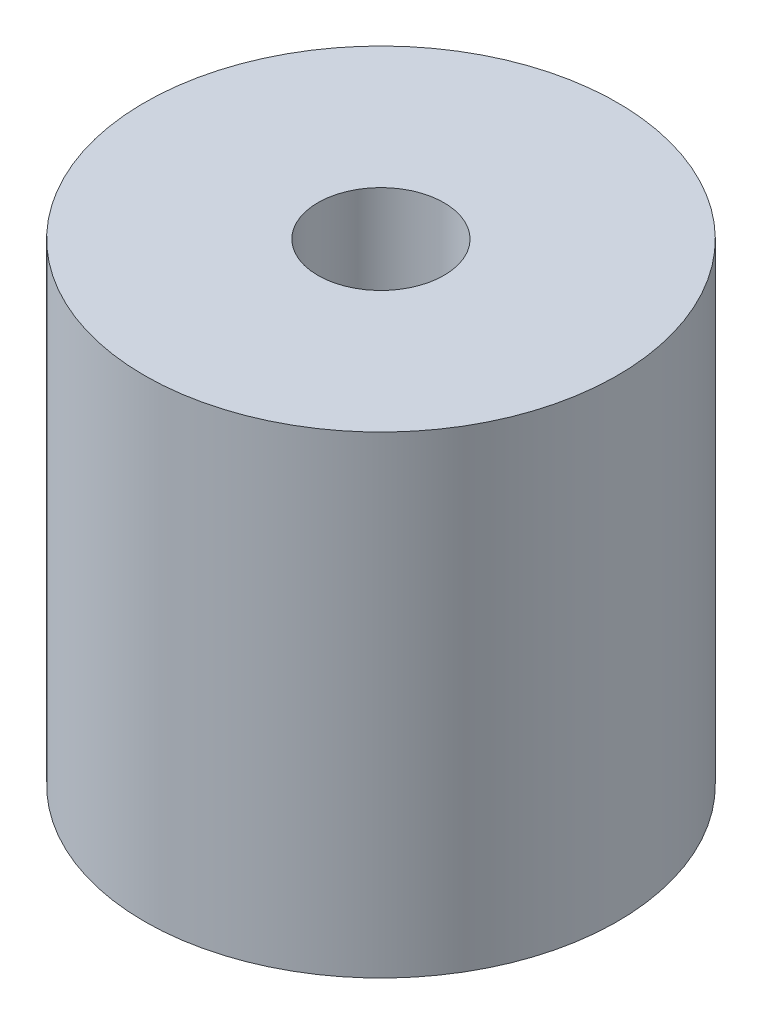
SolidWorks part; units mm, degrees
ref_plane "Alzado" through (0, 0, 0) normal (0, 0, 1) x (1, 0, 0)
ref_plane "Planta" through (0, 0, 0) normal (0, 1, 0) x (1, 0, 0)
ref_plane "Vista lateral" through (0, 0, 0) normal (1, 0, 0) x (0, 0, -1)
sketch "Croquis1" plane through (0, 0, 0) normal (0, 1, 0) x (1, 0, 0)
  circle A0 centre (0, 0) radius 15
  dimension "D1" = 30
extrude "Saliente-Extruir1" add sketch "Croquis1" along normal blind 30
sketch "Croquis2" plane through (0, 30, 0) normal (0, 1, 0) x (1, 0, 0)
  circle A0 centre (0, 0) radius 4
  dimension "D1" = 8
extrude "Cortar-Extruir1" cut sketch "Croquis2" against normal up to next
sketch "Croquis4" plane through (0, 0, 0) normal (0, 0, 1) x (1, 0, 0)
  circle A0 centre (0, 8.248) radius 0.5
  dimension "D1" = 1
